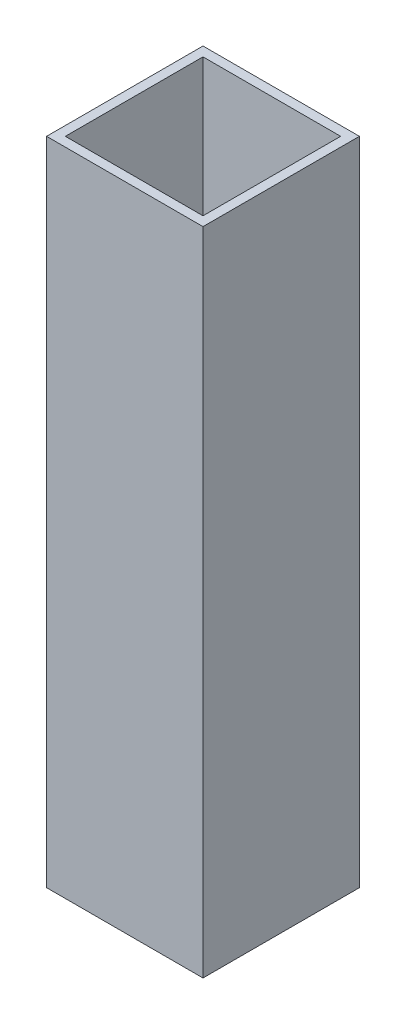
SolidWorks part; units mm, degrees
ref_plane "Front Plane" through (0, 0, 0) normal (0, 0, 1) x (1, 0, 0)
ref_plane "Top Plane" through (0, 0, 0) normal (0, 1, 0) x (1, 0, 0)
ref_plane "Right Plane" through (0, 0, 0) normal (1, 0, 0) x (0, 0, -1)
sketch "Sketch1" plane through (0, 0, 0) normal (0, 1, 0) x (1, 0, 0)
  line L0 (-26.6278, 1.8372) -> (-14.1278, -10.6628) construction
  line L1 (-26.6278, 1.8372) -> (-14.1278, 1.8372)
  line L2 (-26.6278, 1.8372) -> (-26.6278, -10.6628)
  line L3 (-26.6278, -10.6628) -> (-14.1278, -10.6628)
  line L4 (-14.1278, 1.8372) -> (-14.1278, -10.6628)
  line L5 (-26.6278, -10.6628) -> (-14.1278, 1.8372) construction
  line L7 (-25.8778, 1.0872) -> (-14.8778, 1.0872)
  line L8 (-25.8778, 1.0872) -> (-25.8778, -9.9128)
  line L9 (-25.8778, -9.9128) -> (-14.8778, -9.9128)
  line L10 (-14.8778, 1.0872) -> (-14.8778, -9.9128)
  line L11 (-25.8778, 1.0872) -> (-14.8778, -9.9128) construction
  line L12 (-25.8778, -9.9128) -> (-14.8778, 1.0872) construction
  point P4 (-20.3778, -4.4128)
extrude "Boss-Extrude3" add sketch "Sketch1" along normal blind 52
